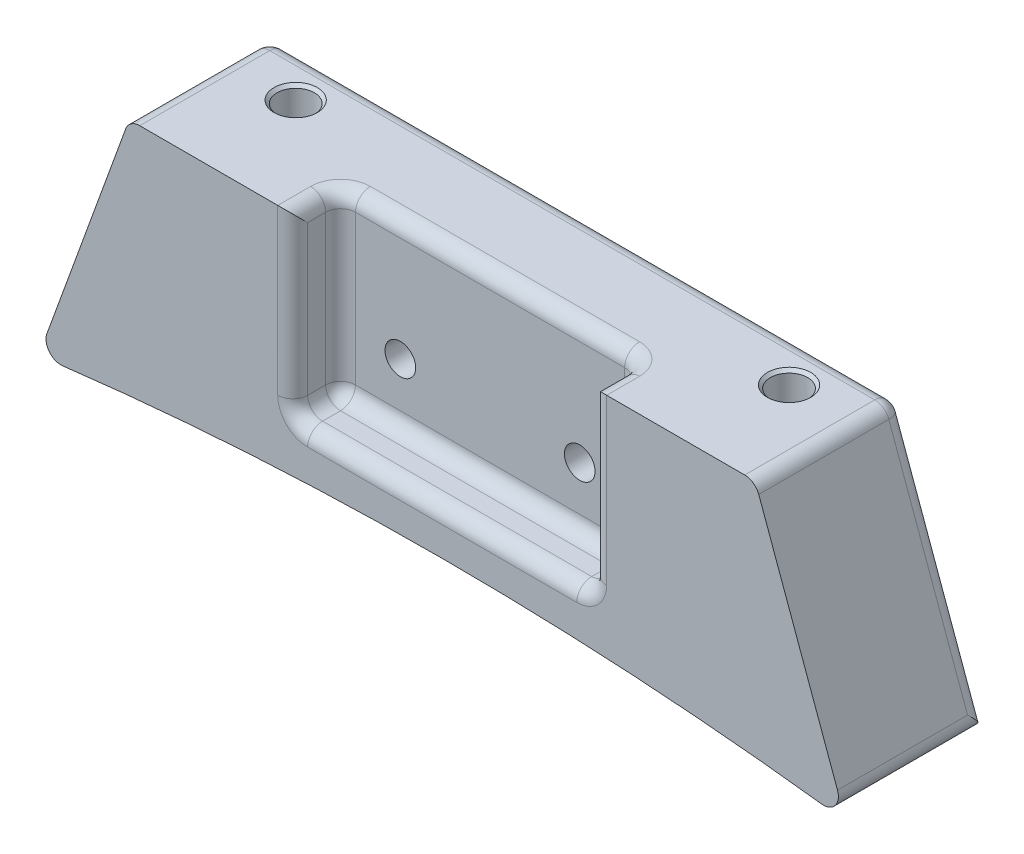
SolidWorks part; units mm, degrees
material "7075-O (SS)"
ref_plane "前视基准面" through (0, 0, 0) normal (0, 0, 1) x (1, 0, 0)
ref_plane "上视基准面" through (0, 0, 0) normal (0, 1, 0) x (1, 0, 0)
ref_plane "右视基准面" through (0, 0, 0) normal (1, 0, 0) x (0, 0, -1)
sketch "草图1" plane through (0, 0, 0) normal (0, 0, 1) x (1, 0, 0)
  line L0 (-22, 14.9488) -> (22, 14.9488)
  line L1 (-22, 14.9488) -> (-28, -3.0512) construction
  line L2 (28, -3.0512) -> (22, 14.9488) construction
  line L3 (0, 14.6299) -> (0, 0) construction
  line L4 (6, 6.9488) -> (-6, 6.9488) construction
  line L5 (0, 0) -> (30.5, 0) construction
  line L6 (30.5, 0) -> (30.5, -4) construction
  line L7 (30.5, -4) -> (-32, -4) construction
  line L8 (22, 14.9488) -> (24.5, 14.9488)
  line L9 (24.5, 14.9488) -> (27, -1.7429)
  line L10 (-22, 14.9488) -> (-24.5, 14.9488)
  line L11 (-24.5, 14.9488) -> (-27, -1.7429)
  arc A0 (-28, -3.0512) -> (28, -3.0512) centre (0, -130) cw construction
  circle A1 centre (-6, 6.9488) radius 0.5
  circle A2 centre (6, 6.9488) radius 0.5
  arc A3 (27, -1.7429) -> (-27, -1.7429) centre (0, -210) ccw
  point P10 (0, 6.9488)
  dimension "D3" = 130
  dimension "D2" = 1
  dimension "D5" = 12
  dimension "D6" = 1
  dimension "D7" = 2.5
  dimension "D8" = 8
  dimension "D12" = 210
  dimension "D1" = 44
  dimension "D4" = 56
  dimension "D9" = 18
  dimension "D10" = 2.5
  dimension "D11" = 27
  dimension "D13" = 27
extrude "凸台-拉伸1" add sketch "草图1" along normal blind 9.7
sketch "草图2" plane through (0, 14.9488, 0) normal (0, 1, 0) x (1, 0, 0)
  line L1 (24.5, 0) -> (-24.5, 0) construction
  line L2 (6, 2) -> (-6, 2)
  line L3 (6, 2) -> (6, -2)
  line L4 (6, -2) -> (-6, -2)
  line L5 (-6, 2) -> (-6, -2)
  line L6 (6, 2) -> (-6, -2) construction
  line L7 (6, -2) -> (-6, 2) construction
  point P0 (0, 0)
  dimension "D1" = 12
  dimension "D2" = 4
extrude "切除-拉伸1" [suppressed] cut sketch "草图2" against normal through all
fillet "圆角1" [suppressed] radius 1
hole_wizard "M3 螺纹孔1" positions "草图8" profile "草图9" tap size "M3" standard "GB"
sketch "草图8" plane through (0, 14.9488, 0) normal (0, 1, 0) x (-1, 0, 0)
  line L2 (-24.5, 0) -> (24.5, 0) construction
  point P0 (-16.5, 3)
  point P2 (16.5, 3)
  dimension "D1" = 33
  dimension "D2" = 16.5
  dimension "D3" = 3
sketch "草图9" plane through (16.5, 14.9488, 3) normal (1, 0, 0) x (0, 0, 1)
  line L0 (0, 0) -> (0, 8.2511)
  line L1 (0, 8.2511) -> (1.25, 7.5)
  line L2 (1.25, 7.5) -> (1.25, 0)
  line L5 (1.25, 0) -> (0, 0)
  line L10 (0, 8.2511) -> (-1.25, 7.5) construction
  line L11 (0, -6.35) -> (0, 107.95) construction
  dimension "螺纹孔钻头直径" = 2.5
  dimension "螺纹孔钻头深度" = 7.5
  dimension "导头角度" = 118
cosmetic thread "孔螺蚊线1" parameters "D1"=6, "D2"=3
cosmetic thread "孔螺蚊线3" parameters "D1"=6, "D2"=3
sketch "草图10" plane through (0, 0, 9.7) normal (0, 0, 1) x (1, 0, 0)
  line L0 (27, -1.7429) -> (20.9148, 15.0031)
  line L1 (24.5, 14.9488) -> (27, -1.7429)
  line L2 (20.9148, 15.0031) -> (24.5, 14.9488)
extrude "切除-拉伸2" cut sketch "草图10" against normal through all
mirror "镜向1" about plane through (0, 0, 0) normal (1, 0, 0) of "切除-拉伸2"
chamfer "倒角1" distance 0.5 angle 45 4 edges at (6.5, 6.9488, 9.7) (-5.5, 6.9488, 9.7) (6.5, 6.9488, 0) (-5.5, 6.9488, 0)
chamfer "倒角2" distance 0.2 angle 45 2 edges at (-16.5, 14.9488, 4.25) (16.5, 14.9488, 4.25)
sketch "草图11" plane through (0, 0, 9.7) normal (0, 0, 1) x (1, 0, 0)
  line L0 (20.9346, 14.9488) -> (-20.9346, 14.9488) construction
  line L1 (0, 0) -> (0, 23.5952) construction
  line L2 (-10, 14.9488) -> (10, 14.9488)
  line L3 (-10, 14.9488) -> (-10, 2.9488)
  line L4 (-10, 2.9488) -> (10, 2.9488)
  line L5 (10, 14.9488) -> (10, 2.9488)
  point P12 (0, 14.9488)
extrude "切除-拉伸3" cut sketch "草图11" against normal blind 3.2
fillet "圆角2" radius 1 11 edges at (0, 14.9488, 6.5) (-10, 14.9488, 8.1) (-10, 8.9488, 6.5) (-10, 8.9488, 9.7) (10, 8.9488, 6.5) (10, 14.9488, 8.1) (10, 8.9488, 9.7) (-10, 2.9488, 8.1) (0, 2.9488, 6.5) (10, 2.9488, 8.1) (0, 2.9488, 9.7)
sketch "草图12" plane through (0, 0, 0) normal (0, 0, -1) x (-1, 0, 0)
  line L1 (-38.9385, -22.4667) -> (31.0262, -22.4667)
  line L2 (-38.9385, -22.4667) -> (-38.9385, 27.9216)
  line L3 (-38.9385, 27.9216) -> (31.0262, 27.9216)
  line L4 (31.0262, -22.4667) -> (31.0262, 27.9216)
extrude "切除-拉伸4" [suppressed] cut sketch "草图12" against normal blind 1.5
fillet "圆角3" radius 1 7 edges at (-20.9346, 14.9488, 4.85) (20.9346, 14.9488, 4.85) (-23.9673, 6.6029, 0) (23.9673, 6.6029, 0) (0, 14.9488, 0) (-27, -1.7429, 4.85) (27, -1.7429, 4.85)
hole_wizard "M2.5 螺纹孔3" positions "3D草图3" profile "草图15" tap size "M2.5" standard "GB"
sketch3d "3D草图3"
  line L0 (6, 6.9488, 6.5) -> (6, 6.9488, 0.5) construction
  line L1 (-6, 6.9488, 6.5) -> (-6, 6.9488, 0.5) construction
  point P0 (6, 6.9488, 6.5)
  point P4 (-6, 6.9488, 6.5)
sketch "草图15" plane through (6, 6.9488, 6.5) normal (1, 0, 0) x (0, -1, 0)
  line L0 (0, 0) -> (0, 8.9659)
  line L1 (0, 8.9659) -> (1.025, 8.35)
  line L2 (1.025, 8.35) -> (1.025, 0)
  line L5 (1.025, 0) -> (0, 0)
  line L10 (0, 8.9659) -> (-1.025, 8.35) construction
  line L11 (0, -6.35) -> (0, 107.95) construction
  dimension "螺纹孔钻头直径" = 2.05
  dimension "螺纹孔钻头深度" = 8.35
  dimension "导头角度" = 118
cosmetic thread "孔螺蚊线6" parameters "D1"=6.7, "D2"=2.5
cosmetic thread "孔螺蚊线7" parameters "D1"=6.7, "D2"=2.5
